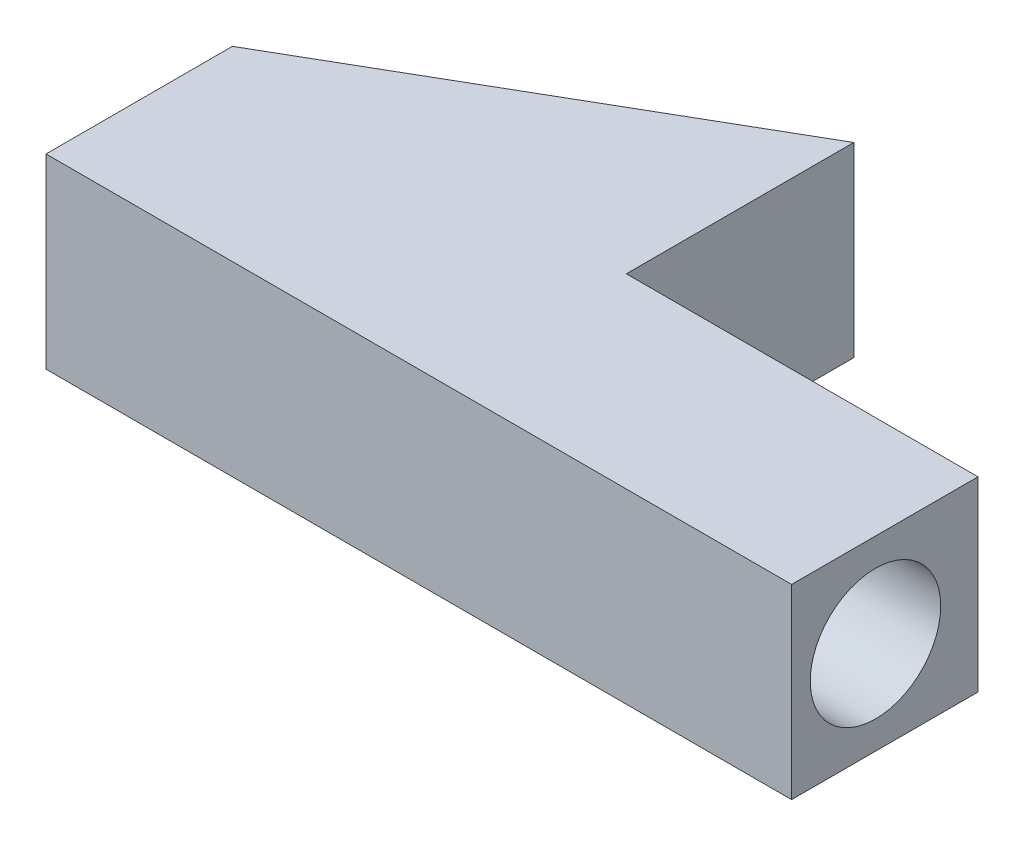
SolidWorks part; units mm, degrees
ref_plane "Front Plane" through (0, 0, 0) normal (0, 0, 1) x (1, 0, 0)
ref_plane "Top Plane" through (0, 0, 0) normal (0, 1, 0) x (1, 0, 0)
ref_plane "Right Plane" through (0, 0, 0) normal (1, 0, 0) x (0, 0, -1)
sketch "Sketch1" plane through (0, 0, 0) normal (0, 1, 0) x (1, 0, 0)
  line L0 (0, 0) -> (0, 3)
  line L1 (0, 3) -> (10.5671, 9.1009)
  line L2 (10.5671, 9.1009) -> (10.5671, 3)
  line L3 (20, 0) -> (0, 0)
  line L5 (20, 0) -> (20, 3)
  line L6 (20, 3) -> (10.5671, 3)
  dimension "D1" = 3
  dimension "D2" = 120
  dimension "D3" = 20
extrude "Boss-Extrude1" add sketch "Sketch1" along normal blind 5
sketch "Sketch2" plane through (-1.299, 0, -2.25) normal (-0.5, 0, -0.866) x (-0.866, 0, 0.5)
  line L0 (-1.5, 5) -> (-1.5, 0) construction
  circle A0 centre (-7.5, 2.5) radius 1.5
  point P4 (-1.5, 2.5)
  dimension "D1" = 3
  dimension "D2" = 6
extrude "Cut-Extrude1" cut sketch "Sketch2" against normal blind 5
sketch "Sketch5" plane through (0, 0, 0) normal (0, 0, 1) x (1, 0, 0)
  line L4 (0, 0) -> (20, 0)
  line L5 (20, 0) -> (20, 5)
  line L6 (20, 5) -> (0, 5)
  line L7 (0, 5) -> (0, 0)
  line L8 (0, 0) -> (20, 0)
  line L9 (20, 0) -> (20, 5)
  line L10 (20, 5) -> (0, 5)
  line L11 (0, 5) -> (0, 0)
  dimension "D1" = 0
extrude "Boss-Extrude3" add sketch "Sketch5" along normal blind 2
sketch "Sketch6" plane through (20, 0, 0) normal (1, 0, 0) x (0, 0, -1)
  line L0 (-2, 0) -> (-2, 5) construction
  circle A0 centre (0.25, 2.5) radius 1.75
  point P4 (-2, 2.5)
  dimension "D1" = 3.5
  dimension "D2" = 2.25
extrude "Cut-Extrude2" cut sketch "Sketch6" against normal up to surface (20 mm away) up to face at (0, 2.5, -0.5)
